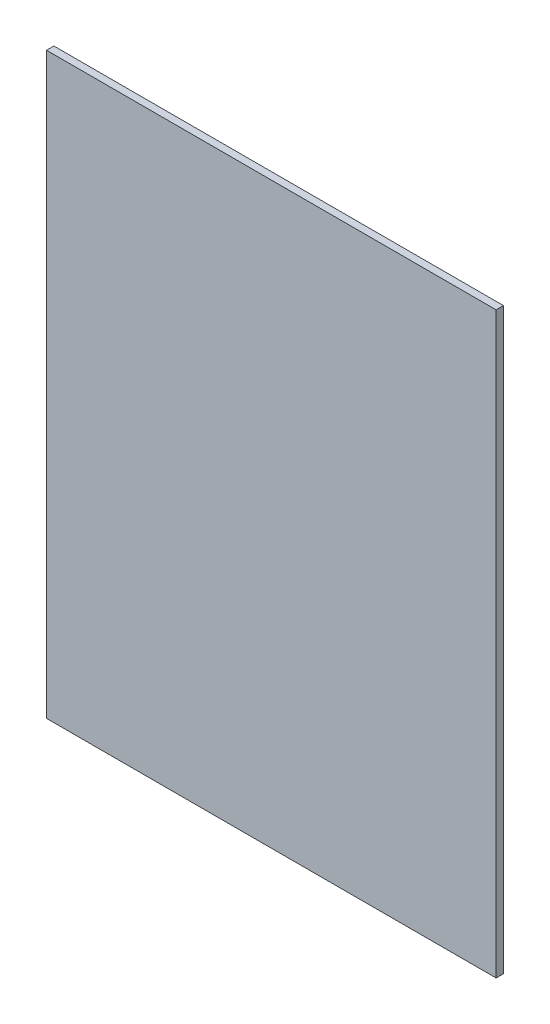
SolidWorks part; units mm, degrees
ref_plane "Front" through (0, 0, 0) normal (0, 0, 1) x (1, 0, 0)
ref_plane "Top" through (0, 0, 0) normal (0, 1, 0) x (1, 0, 0)
ref_plane "Right" through (0, 0, 0) normal (1, 0, 0) x (0, 0, -1)
sketch "Sketch2" plane through (0, 0, 0) normal (0, 0, 1) x (1, 0, 0)
  line L1 (0, 0) -> (-730.25, 0)
  line L2 (0, 0) -> (0, 939.8)
  line L3 (0, 939.8) -> (-730.25, 939.8)
  line L4 (-730.25, 0) -> (-730.25, 939.8)
  dimension "D1" = 730.25
  dimension "D2" = 939.8
extrude "Boss-Extrude1" add sketch "Sketch2" along normal blind 11.938
